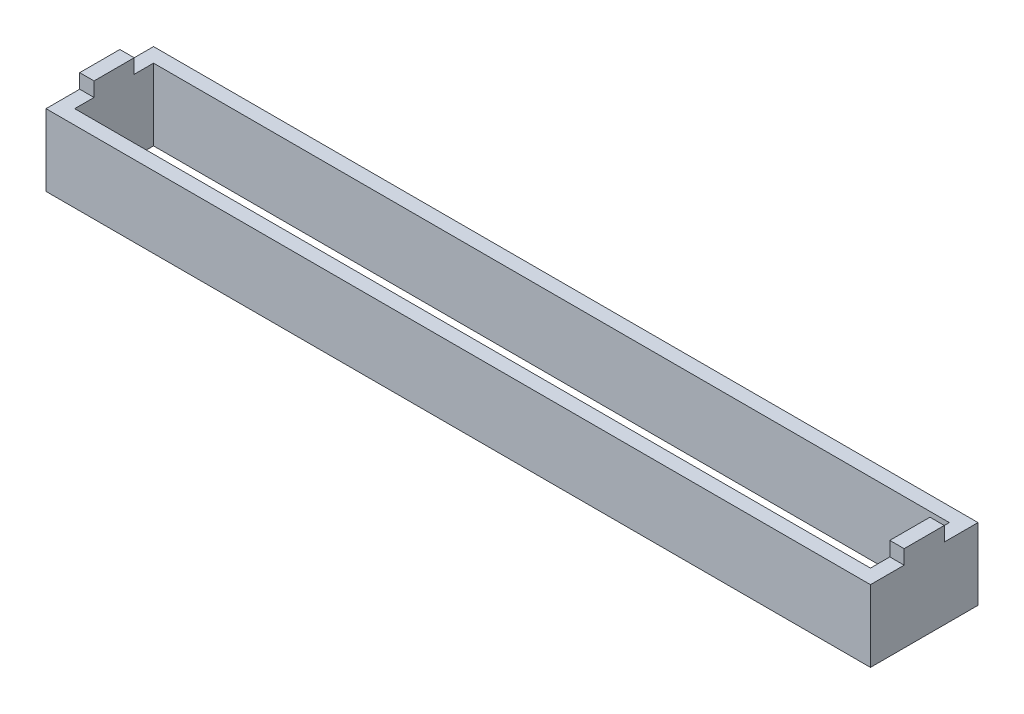
SolidWorks part; units mm, degrees
ref_plane "Front Plane" through (0, 0, 0) normal (0, 0, 1) x (1, 0, 0)
ref_plane "Top Plane" through (0, 0, 0) normal (0, 1, 0) x (1, 0, 0)
ref_plane "Right Plane" through (0, 0, 0) normal (1, 0, 0) x (0, 0, -1)
sketch "Sketch1" plane through (0, 0, 0) normal (0, 1, 0) x (1, 0, 0)
  line L1 (-57.5, -7.5) -> (57.5, -7.5)
  line L2 (-57.5, -7.5) -> (-57.5, 7.5)
  line L3 (-57.5, 7.5) -> (57.5, 7.5)
  line L4 (57.5, -7.5) -> (57.5, 7.5)
  line L5 (-57.5, -7.5) -> (57.5, 7.5) construction
  line L6 (-57.5, 7.5) -> (57.5, -7.5) construction
  line L7 (-55.5, -5.5) -> (55.5, -5.5)
  line L8 (-55.5, -5.5) -> (-55.5, 5.5)
  line L9 (-55.5, 5.5) -> (55.5, 5.5)
  line L10 (55.5, -5.5) -> (55.5, 5.5)
  line L11 (-55.5, -5.5) -> (55.5, 5.5) construction
  line L12 (-55.5, 5.5) -> (55.5, -5.5) construction
  point P0 (0, 0)
  point P6 (0, 0)
  dimension "D1" = 115
  dimension "D2" = 15
  dimension "D3" = 2
  dimension "D4" = 2
extrude "Boss-Extrude1" add sketch "Sketch1" along normal blind 10
sketch "Sketch2" plane through (0, 10, 0) normal (0, 1, 0) x (1, 0, 0)
  line L0 (-57.5, 7.5) -> (-57.5, -7.5) construction
  line L1 (-57.5, -2.8) -> (-55.5, -2.8)
  line L2 (-57.5, -2.8) -> (-57.5, 2.8)
  line L3 (-57.5, 2.8) -> (-55.5, 2.8)
  line L4 (-55.5, -2.8) -> (-55.5, 2.8)
  line L5 (-55.5, 5.5) -> (-55.5, -5.5) construction
  line L6 (-5.5, 0) -> (5.5, 0) construction
  line L7 (55.5, -5.5) -> (55.5, 5.5) construction
  line L8 (55.5, 2.8) -> (57.5, 2.8)
  line L9 (55.5, 2.8) -> (55.5, -2.8)
  line L10 (55.5, -2.8) -> (57.5, -2.8)
  line L11 (57.5, 2.8) -> (57.5, -2.8)
  line L12 (57.5, -7.5) -> (57.5, 7.5) construction
  point P10 (-55.5, 0)
  dimension "D1" = 5.6
extrude "Boss-Extrude2" add sketch "Sketch2" along normal blind 2
